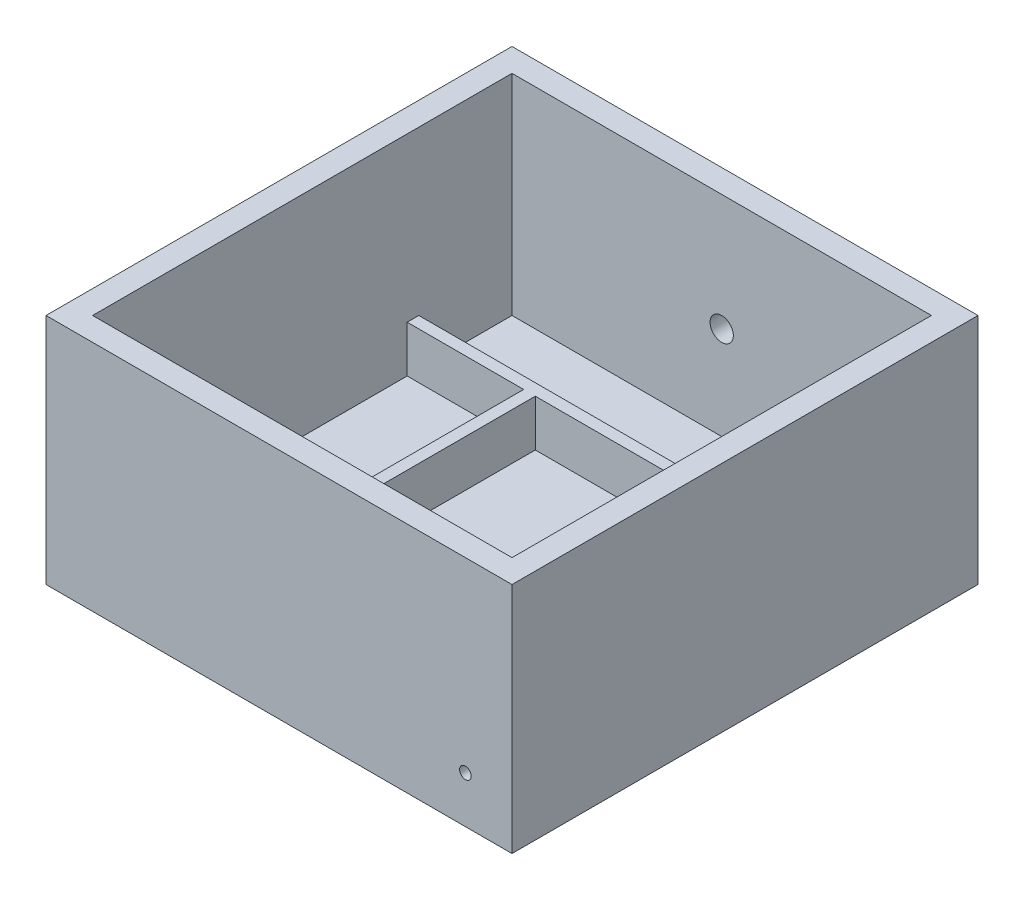
SolidWorks part; units mm, degrees
ref_plane "Front Plane" through (0, 0, 0) normal (0, 0, 1) x (1, 0, 0)
ref_plane "Top Plane" through (0, 0, 0) normal (0, 1, 0) x (1, 0, 0)
ref_plane "Right Plane" through (0, 0, 0) normal (1, 0, 0) x (0, 0, -1)
sketch "Sketch1" plane through (0, 0, 0) normal (0, 1, 0) x (1, 0, 0)
  line L1 (-4465.0526, -2346.6842) -> (-4265.0526, -2346.6842)
  line L2 (-4465.0526, -2346.6842) -> (-4465.0526, -2546.6842)
  line L3 (-4465.0526, -2546.6842) -> (-4265.0526, -2546.6842)
  line L4 (-4265.0526, -2346.6842) -> (-4265.0526, -2546.6842)
  line L5 (-4455.0526, -2356.6842) -> (-4275.0526, -2356.6842)
  line L6 (-4455.0526, -2356.6842) -> (-4455.0526, -2536.6842)
  line L7 (-4455.0526, -2536.6842) -> (-4275.0526, -2536.6842)
  line L8 (-4275.0526, -2356.6842) -> (-4275.0526, -2536.6842)
  dimension "D1" = 10
  dimension "D2" = 10
  dimension "D3" = 10
  dimension "D4" = 10
  dimension "D5" = 200
  dimension "D6" = 200
extrude "Boss-Extrude1" add sketch "Sketch1" along normal blind 100
sketch "Sketch2" plane through (0, 0, 0) normal (0, 1, 0) x (1, 0, 0)
  line L1 (-4465.0526, -2546.6842) -> (-4265.0526, -2546.6842)
  line L2 (-4465.0526, -2546.6842) -> (-4465.0526, -2346.6842)
  line L3 (-4465.0526, -2346.6842) -> (-4265.0526, -2346.6842)
  line L4 (-4265.0526, -2546.6842) -> (-4265.0526, -2346.6842)
extrude "Boss-Extrude2" add sketch "Sketch2" along normal blind 10
sketch "Sketch3" plane through (0, 0, 2346.6842) normal (0, 0, -1) x (-1, 0, 0)
  line L0 (4265.0526, 0) -> (4465.0526, 0) construction
  line L1 (4265.0526, 100) -> (4265.0526, 0) construction
  circle A0 centre (4365.0526, 50) radius 5
  point P5 (4365.0526, 0)
  point P8 (4265.0526, 50)
  dimension "D1" = 10
extrude "Cut-Extrude1" cut sketch "Sketch3" against normal blind 10
sketch "Sketch4" plane through (0, 10, 0) normal (0, 1, 0) x (1, 0, 0)
  line L0 (-4455.0526, -2396.6842) -> (-4275.0526, -2396.6842)
  line L1 (-4455.0526, -2356.6842) -> (-4455.0526, -2536.6842) construction
  line L2 (-4275.0526, -2536.6842) -> (-4275.0526, -2356.6842) construction
  line L3 (-4455.0526, -2356.6842) -> (-4275.0526, -2356.6842) construction
  line L4 (-4455.0526, -2401.6842) -> (-4275.0526, -2401.6842)
  line L5 (-4275.0526, -2356.6842) -> (-4275.0526, -2536.6842) construction
  line L6 (-4405.0526, -2401.6842) -> (-4405.0526, -2536.6842)
  line L7 (-4455.0526, -2536.6842) -> (-4275.0526, -2536.6842) construction
  line L8 (-4405.0526, -2536.6842) -> (-4400.0526, -2536.6842)
  line L9 (-4275.0526, -2536.6842) -> (-4455.0526, -2536.6842) construction
  line L10 (-4400.0526, -2536.6842) -> (-4400.0526, -2401.6842)
  line L11 (-4400.0526, -2401.6842) -> (-4405.0526, -2401.6842)
  line L12 (-4455.0526, -2536.6842) -> (-4455.0526, -2356.6842) construction
  line M3 (-4455.0526, -2356.6842) -> (-4455.0526, -2536.6842)
  line M4 (-4455.0526, -2536.6842) -> (-4275.0526, -2536.6842)
  line M5 (-4275.0526, -2536.6842) -> (-4275.0526, -2356.6842)
  dimension "D1" = 40
  dimension "D2" = 5
  dimension "D3" = 5
  dimension "D4" = 50
extrude "Boss-Extrude3" add sketch "Sketch4" along normal blind 20 contours L10 L4 L6 M4 | L4 L0 M3 M5
sketch "Sketch6" plane through (0, 0, 2546.6842) normal (0, 0, 1) x (1, 0, 0)
  line L0 (-4465.0526, 0) -> (-4265.0526, 0) construction
  line L1 (-4265.0526, 100) -> (-4265.0526, 0) construction
  circle A0 centre (-4285.0526, 20) radius 2.5
  dimension "D1" = 5
  dimension "D2" = 20
  dimension "D3" = 20
extrude "Cut-Extrude2" cut sketch "Sketch6" against normal blind 10
